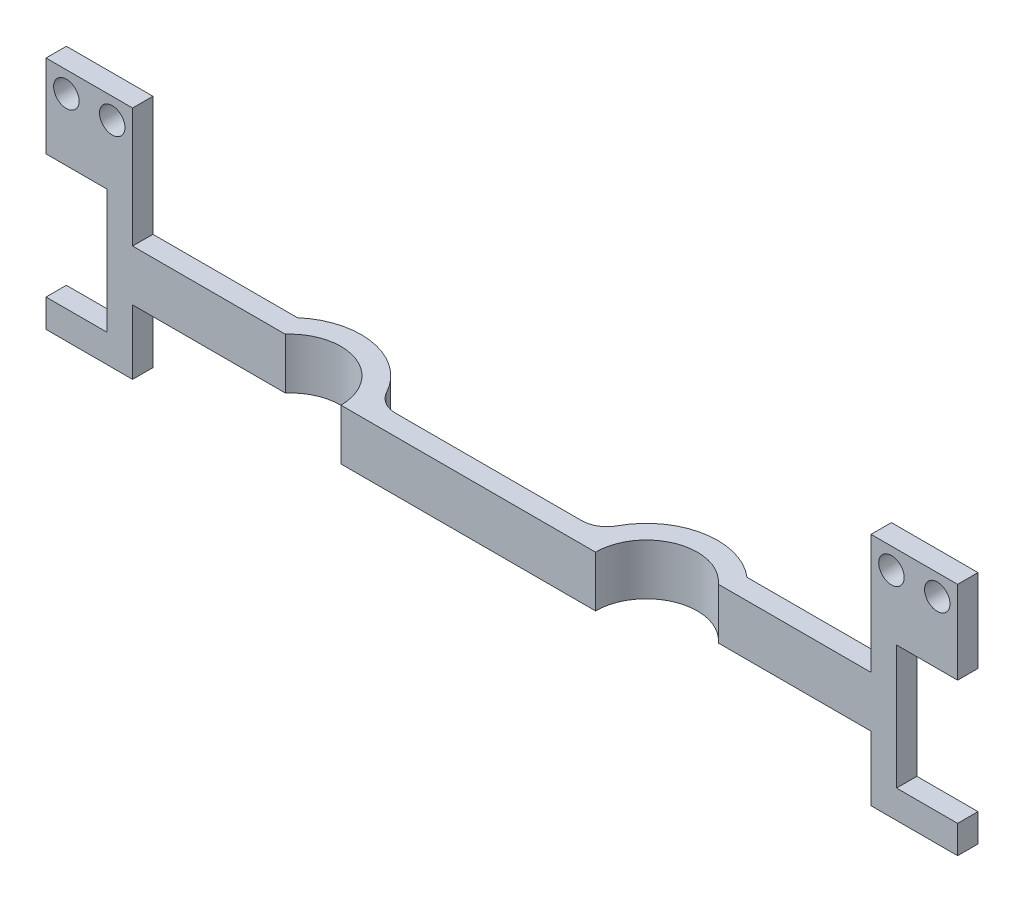
SolidWorks part; units mm, degrees
ref_plane "Front Plane" through (0, 0, 0) normal (0, 0, 1) x (1, 0, 0)
ref_plane "Top Plane" through (0, 0, 0) normal (0, 1, 0) x (1, 0, 0)
ref_plane "Right Plane" through (0, 0, 0) normal (1, 0, 0) x (0, 0, -1)
sketch "Sketch1" plane through (0, 0, 0) normal (0, 1, 0) x (1, 0, 0)
  line L0 (0, 0) -> (63.5, 0)
  line L4 (8.5512, 5.08) -> (54.9488, 5.08)
  line L8 (93.2388, 5.08) -> (101.6, 5.08) construction
  line L9 (4.3388, 5.08) -> (59.1612, 5.08) construction
  line L10 (-29.7388, 5.08) -> (-60.3411, 5.08) construction
  line L11 (-60.3411, 5.08) -> (-60.3411, 13.462) construction
  line L12 (-60.3411, 13.462) -> (-24.3148, 13.462)
  line L13 (-60.3411, 13.462) -> (-60.3411, 8.382)
  line L14 (-60.3411, 8.382) -> (-22.2411, 8.382)
  line L16 (-25.4, 0) -> (-60.3411, 0) construction
  line L17 (123.8411, 8.382) -> (85.7411, 8.382)
  line L18 (0, 0) -> (63.5, 0) construction
  line L19 (88.9, 0) -> (101.6, 0) construction
  line L20 (123.8411, 13.462) -> (123.8411, 8.382)
  line L21 (123.8411, 13.462) -> (87.8148, 13.462)
  arc A0 (-22.2411, 8.382) -> (0, 0) centre (-12.7, 0) cw
  arc A3 (-24.3148, 13.462) -> (2.9588, 8.4221) centre (-12.7, 0) cw
  arc A4 (59.1612, 5.08) -> (93.2388, 5.08) centre (76.2, 0) cw construction
  arc A7 (-29.7388, 5.08) -> (4.3388, 5.08) centre (-12.7, 0) cw construction
  arc A8 (8.5512, 5.08) -> (2.9588, 8.4221) centre (8.5512, 11.43) cw
  arc A10 (85.7411, 8.382) -> (63.5, 0) centre (76.2, 0) ccw
  arc A11 (-25.4, 0) -> (0, 0) centre (-12.7, 0) cw construction
  arc A12 (63.5, 0) -> (88.9, 0) centre (76.2, 0) cw construction
  arc A13 (87.8148, 13.462) -> (60.5412, 8.4221) centre (76.2, 0) ccw
  arc A14 (54.9488, 5.08) -> (60.5412, 8.4221) centre (54.9488, 11.43) ccw
  dimension "D1" = 12.7
  dimension "D6" = 5.08
  dimension "D3" = 12.7
  dimension "D11" = 5.08
  dimension "D12" = 6.35
  dimension "D2" = 88.9
  dimension "D4" = 8.382
  dimension "D5" = 38.1
  dimension "D7" = 8.382
  dimension "D8" = 5.08
  dimension "D9" = 38.1
  dimension "D10" = 8.382
extrude "Boss-Extrude1" add sketch "Sketch1" along normal blind 12.7
sketch "Sketch3" plane through (0, 0, -13.462) normal (0, 0, -1) x (-1, 0, 0)
  line L9 (-31.75, 12.7) -> (-31.75, 0) construction
  line L10 (81.9311, -16.1036) -> (60.3411, -16.1036)
  line L11 (81.9311, -9.1059) -> (81.9311, -16.1036)
  line L12 (66.6911, -9.1059) -> (81.9311, -9.1059)
  line L13 (66.6911, 21.8059) -> (66.6911, -9.1059)
  line L14 (81.9311, 21.8059) -> (66.6911, 21.8059)
  line L15 (81.9311, 28.8036) -> (81.9311, 21.8059)
  line L18 (60.3411, -16.1036) -> (60.3411, 28.8036)
  line L19 (60.3411, 12.7) -> (60.3411, 0) construction
  line L22 (60.3411, 12.7) -> (60.3411, 0) construction
  line L23 (-54.9488, 12.7) -> (-8.5512, 12.7) construction
  line L24 (-54.9488, 0) -> (-8.5512, 0) construction
  line L25 (-123.8411, -16.1036) -> (-123.8411, 28.8036)
  line L26 (-145.4311, -16.1036) -> (-123.8411, -16.1036)
  line L27 (-145.4311, -9.1059) -> (-145.4311, -16.1036)
  line L28 (-130.1911, -9.1059) -> (-145.4311, -9.1059)
  line L29 (-130.1911, 21.8059) -> (-130.1911, -9.1059)
  line L30 (-145.4311, 21.8059) -> (-130.1911, 21.8059)
  line L31 (-145.4311, 28.8036) -> (-145.4311, 21.8059)
  line L35 (60.3411, 28.8036) -> (60.3411, 42.5196)
  line L36 (60.3411, 42.5196) -> (81.9311, 42.5196)
  line L37 (81.9311, 28.8036) -> (81.9311, 42.5196)
  line L39 (-145.4311, 28.8036) -> (-145.4311, 42.5196)
  line L40 (-145.4311, 42.5196) -> (-123.8411, 42.5196)
  line L41 (-123.8411, 28.8036) -> (-123.8411, 42.5196)
  point P6 (60.3411, 6.35)
  point P7 (60.3411, 6.35)
  dimension "D1" = 30.9118
  dimension "D2" = 6.9977
  dimension "D3" = 6.9977
  dimension "D4" = 21.59
  dimension "D5" = 15.24
  dimension "D6" = 15.24
  dimension "D7" = 13.716
  dimension "D8" = 13.716
extrude "Boss-Extrude3" add sketch "Sketch3" against normal up to surface (5.08 mm away) up to face at (-41.2911, 6.35, -8.382)
sketch "Sketch4" plane through (0, 0, -13.462) normal (0, 0, -1) x (-1, 0, 0)
  line L0 (-123.8411, 42.5196) -> (-145.4311, 42.5196) construction
  line L1 (-145.4311, 37.3228) -> (-140.3511, 37.3228) construction
  line L2 (-145.4311, 42.5196) -> (-145.4311, 21.8059) construction
  line L3 (-128.9211, 37.3228) -> (-123.8411, 37.3228) construction
  line L4 (-123.8411, 12.7) -> (-123.8411, 42.5196) construction
  line L5 (65.4211, 37.3228) -> (60.3411, 37.3228) construction
  line L6 (60.3411, 42.5196) -> (60.3411, 12.7) construction
  line L7 (76.8511, 37.3228) -> (81.9311, 37.3228) construction
  line L8 (81.9311, 21.8059) -> (81.9311, 42.5196) construction
  circle A0 centre (-140.3511, 37.3228) radius 3.175
  circle A1 centre (-128.9211, 37.3228) radius 3.175
  circle A2 centre (65.4211, 37.3228) radius 3.175
  circle A3 centre (76.8511, 37.3228) radius 3.175
  dimension "D1" = 6.35
  dimension "D2" = 5.1968
  dimension "D3" = 5.08
extrude "Cut-Extrude2" cut sketch "Sketch4" against normal up to surface (5.08 mm away) up to face at (125.7461, 8.636, -8.382)
